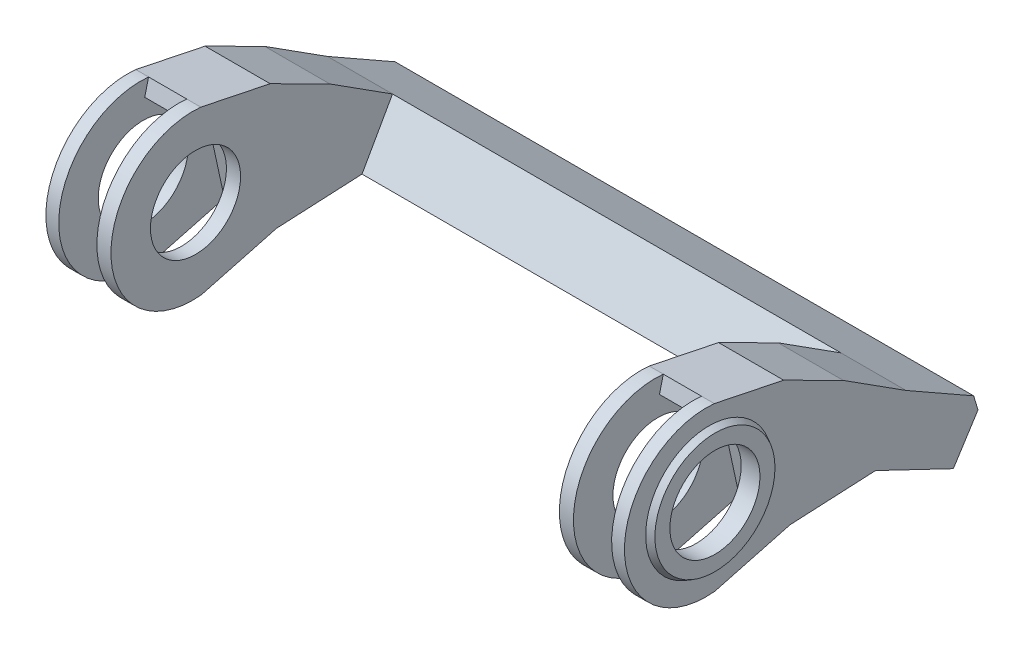
SolidWorks part; units mm, degrees
ref_plane "Front Plane" through (0, 0, 0) normal (0, 0, 1) x (1, 0, 0)
ref_plane "Top Plane" through (0, 0, 0) normal (0, 1, 0) x (1, 0, 0)
ref_plane "Right Plane" through (0, 0, 0) normal (1, 0, 0) x (0, 0, -1)
ref_plane "Plane1" through (117.9219, 0, 0) normal (1, 0, 0) x (0, 0, -1)
ref_plane "Plane2" through (0, 0, 75.5764) normal (0, 0, 1) x (1, 0, 0)
sketch "Sketch1" plane through (0, 0, 0) normal (1, 0, 0) x (0, 0, -1)
  line L0 (6.8351, 301.8213) -> (21.924, 328.6163)
  line L1 (21.924, 328.6163) -> (55.3956, 309.5821)
  line L2 (55.3956, 309.5821) -> (57.5424, 302.4751)
  line L3 (57.5424, 302.4751) -> (45.3471, 283.3769)
  line L4 (45.3471, 283.3769) -> (6.8351, 301.8213)
extrude "Boss-Extrude1" add sketch "Sketch1" along normal blind 110.9489 and the other way blind 110.9489
sketch "Sketch2" plane through (110.9489, 0, 0) normal (1, 0, 0) x (0, 0, -1)
  line L0 (6.8351, 301.8213) -> (45.3471, 283.3769)
  line L1 (45.3471, 283.3769) -> (57.5424, 302.4751)
  line L2 (57.5424, 302.4751) -> (55.3956, 309.5821)
  line L3 (55.3956, 309.5821) -> (21.924, 328.6163)
  line L4 (21.924, 328.6163) -> (-9.1238, 348.442)
  line L5 (-9.1238, 348.442) -> (-38.6324, 363.3)
  line L6 (-38.6324, 363.3) -> (-72.9445, 370.4168)
  line L7 (6.8351, 301.8213) -> (-35.4457, 299.7431)
  line L8 (-35.4457, 299.7431) -> (-72.6341, 289.8648)
  arc A1 (-72.9445, 370.4168) -> (-72.6341, 289.8648) centre (-76.9202, 330.1249) ccw
  point P17 (-117.3152, 327.389)
extrude "Boss-Extrude2" add sketch "Sketch2" along normal blind 32.21
sketch "Sketch3" plane through (117.9219, 0, 0) normal (1, 0, 0) x (0, 0, -1)
  line L0 (-72.9445, 370.4168) -> (-74.851, 362.6777)
  line L1 (-35.4457, 299.7431) -> (-44.9859, 343.7214)
  line L2 (-72.9445, 370.4168) -> (-87.8292, 385.3015)
  line L3 (-87.8292, 385.3015) -> (-147.0203, 329.1171)
  line L4 (-147.0203, 329.1171) -> (-71.1433, 263.8523)
  line L5 (-71.1433, 263.8523) -> (-35.4457, 299.7431)
  arc A0 (-74.851, 362.6777) -> (-44.9859, 343.7214) centre (-73.6802, 331.5183) cw
  point P7 (-52.7621, 354.6422)
extrude "Cut-Extrude1" cut sketch "Sketch3" along normal blind 18.8768
sketch "Sketch4" plane through (0, 0, 75.5764) normal (0, 0, 1) x (1, 0, 0)
  line L0 (141.4813, 363.1504) -> (146.0904, 360.5888)
  line L1 (146.0904, 360.5888) -> (146.0904, 330.8703)
  line L2 (146.0904, 330.8703) -> (141.4813, 330.8703)
  line L3 (141.4813, 330.8703) -> (141.4813, 363.1504)
revolve "Revolve1" add sketch "Sketch4" angle 360 about L2
mirror "Mirror1" about plane through (0, 0, 0) normal (1, 0, 0) of "Revolve1", "Boss-Extrude2", "Cut-Extrude1"
sketch "Sketch5" plane through (0, 0, 0) normal (1, 0, 0) x (0, 0, -1)
  circle A0 centre (-75.5764, 330.8703) radius 22.2928
  point P19 (-97.8245, 332.2808)
extrude "Cut-Extrude2" cut sketch "Sketch5" against normal through all and the other way through all
